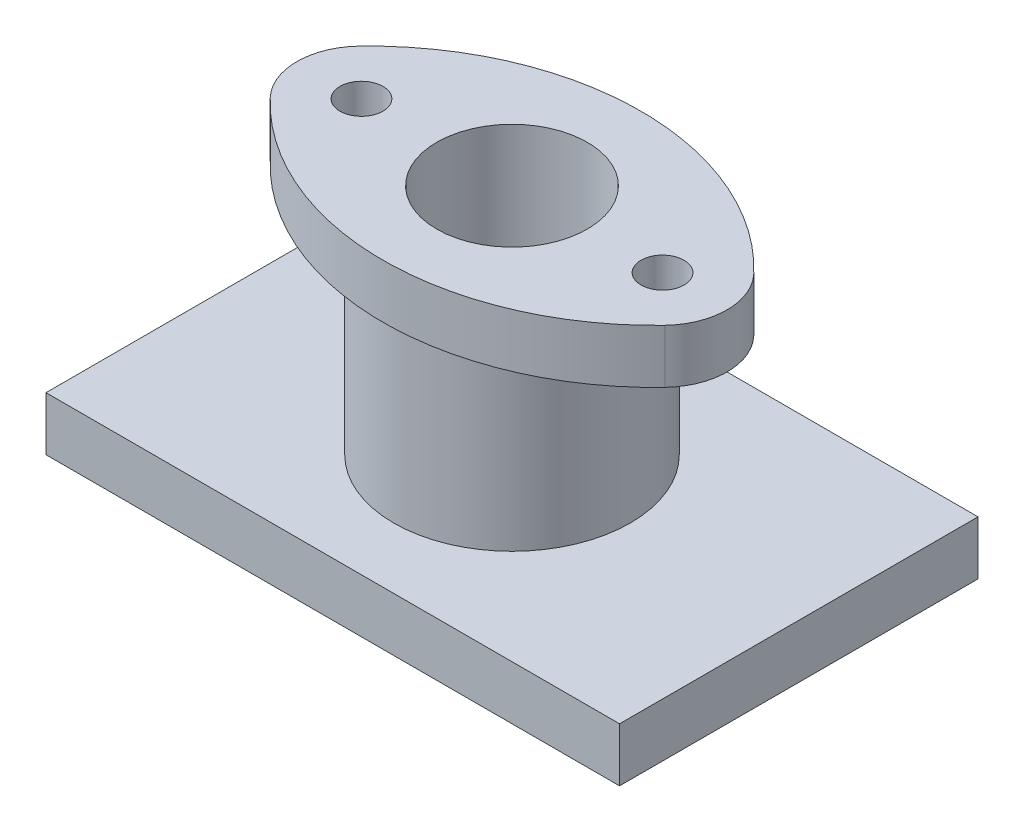
SolidWorks part; units mm, degrees
material "Gray Cast Iron"
ref_plane "Front Plane" through (0, 0, 0) normal (0, 0, 1) x (1, 0, 0)
ref_plane "Top Plane" through (0, 0, 0) normal (0, 1, 0) x (1, 0, 0)
ref_plane "Right Plane" through (0, 0, 0) normal (1, 0, 0) x (0, 0, -1)
sketch "Sketch1" plane through (0, 0, 0) normal (0, 1, 0) x (1, 0, 0)
  line L1 (-80, 50) -> (80, 50)
  line L2 (-80, 50) -> (-80, -50)
  line L3 (-80, -50) -> (80, -50)
  line L4 (80, 50) -> (80, -50)
  line L5 (-80, 50) -> (80, -50) construction
  line L6 (-80, -50) -> (80, 50) construction
  point P0 (0, 0)
  dimension "D1" = 160
  dimension "D2" = 100
extrude "Boss-Extrude1" add sketch "Sketch1" along normal blind 15
sketch "Sketch3" plane through (0, 0, 0) normal (0, -1, 0) x (1, 0, 0)
  circle A0 centre (0, 0) radius 16.5
  dimension "D1" = 33
extrude "Cut-Extrude1" cut sketch "Sketch3" against normal up to surface (15 mm away) up to face at (0, 15, 0)
sketch "Sketch2" plane through (0, 15, 0) normal (0, 1, 0) x (1, 0, 0)
  circle A0 centre (0, 0) radius 33
  dimension "D1" = 66
extrude "Boss-Extrude2" add sketch "Sketch2" along normal blind 50
sketch "Sketch6" plane through (0, 65, 0) normal (0, 1, 0) x (1, 0, 0)
  line L0 (-60, 0) -> (60, 0) construction
  line L1 (0, -36) -> (0, 36) construction
  circle A0 centre (-42, 0) radius 6
  circle A1 centre (42, 0) radius 6
  arc A4 (-55.0345, 12.4138) -> (-55.0345, -12.4138) centre (-42, 0) ccw
  arc A5 (55.0345, 12.4138) -> (55.0345, -12.4138) centre (42, 0) cw
  arc A6 (-55.0345, 12.4138) -> (55.0345, 12.4138) centre (0, -40) cw
  arc A7 (-55.0345, -12.4138) -> (55.0345, -12.4138) centre (0, 40) ccw
  point P11 (0, 0)
  dimension "D2" = 12
  dimension "D4" = 72
  dimension "D1" = 120
  dimension "D3" = 84
extrude "Boss-Extrude4" add sketch "Sketch6" along normal blind 15
sketch "Sketch7" plane through (0, 80, 0) normal (0, 1, 0) x (1, 0, 0)
  circle A0 centre (0, 0) radius 21
  dimension "D1" = 42
extrude "Cut-Extrude3" cut sketch "Sketch7" against normal up to surface (65 mm away) up to face at (0, 15, 33)
